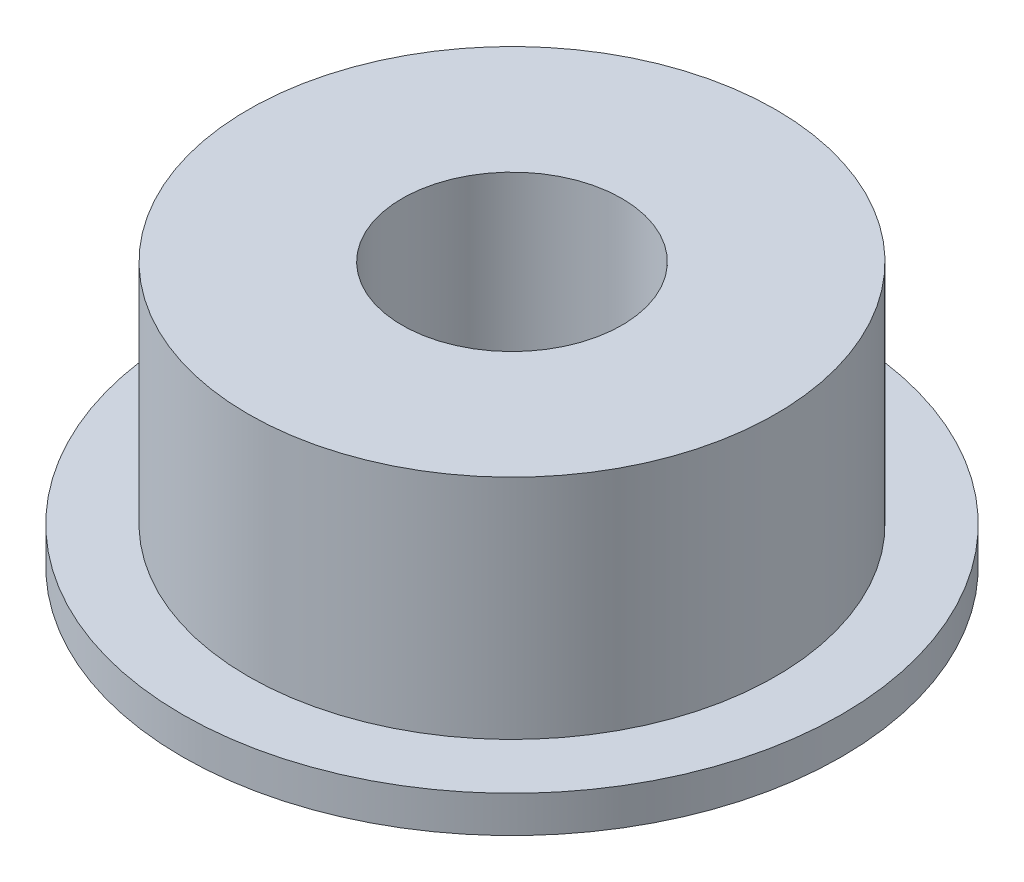
SolidWorks part; units mm, degrees
ref_plane "前视基准面" through (0, 0, 0) normal (0, 0, 1) x (1, 0, 0)
ref_plane "上视基准面" through (0, 0, 0) normal (0, 1, 0) x (1, 0, 0)
ref_plane "右视基准面" through (0, 0, 0) normal (1, 0, 0) x (0, 0, -1)
other "Configuration Table"
sketch "草图1" plane through (0, 0, 0) normal (0, 1, 0) x (1, 0, 0)
  circle A0 centre (0, 0) radius 4.5
  dimension "D1" = 9
extrude "凸台-拉伸1" add sketch "草图1" along normal blind 0.5
sketch "草图2" plane through (0, 0.5, 0) normal (0, 1, 0) x (1, 0, 0)
  circle A0 centre (0, 0) radius 3.6
  dimension "D1" = 7.2
extrude "凸台-拉伸2" add sketch "草图2" along normal blind 3.1
sketch "草图3" plane through (0, 0, 0) normal (0, -1, 0) x (1, 0, 0)
  circle A0 centre (0, 0) radius 1.5
  dimension "D1" = 3
extrude "切除-拉伸1" cut sketch "草图3" against normal through all
